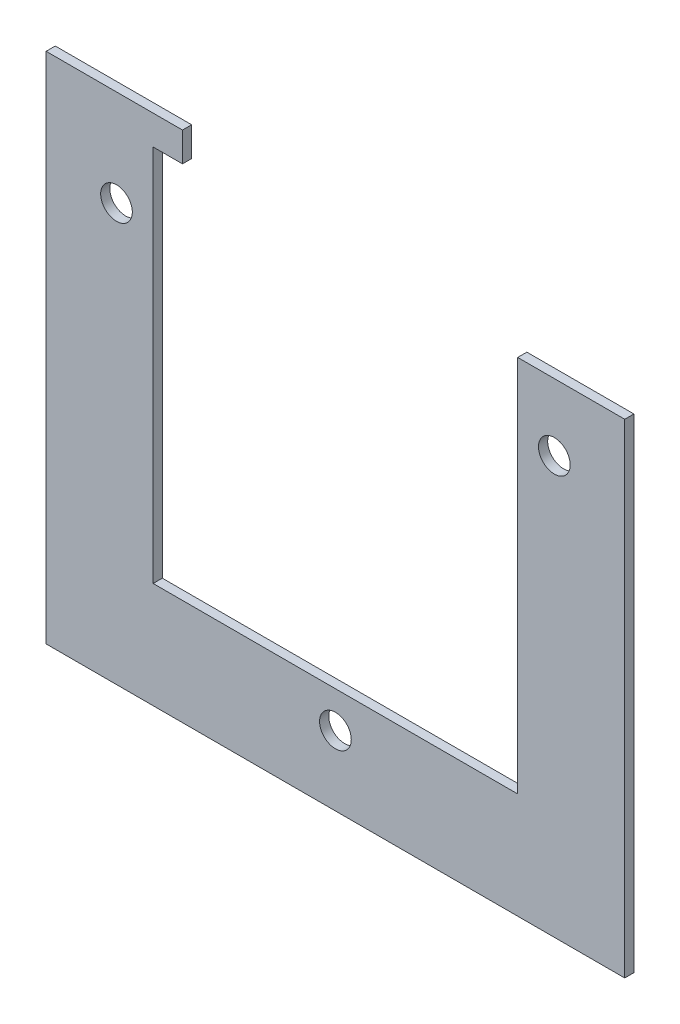
SolidWorks part; units mm, degrees
ref_plane "Front Plane" through (0, 0, 0) normal (0, 0, 1) x (1, 0, 0)
ref_plane "Top Plane" through (0, 0, 0) normal (0, 1, 0) x (1, 0, 0)
ref_plane "Right Plane" through (0, 0, 0) normal (1, 0, 0) x (0, 0, -1)
sketch "Sketch1" plane through (0, 0, 0) normal (0, 0, 1) x (1, 0, 0)
  line L0 (7520.0826, 3427.6123) -> (7529.3536, 3427.6123)
  line L1 (7479.2394, 3430.1523) -> (7491.0504, 3430.1523)
  line L2 (7520.0826, 3427.6123) -> (7520.0826, 3394.8717)
  line L3 (7529.3536, 3427.6123) -> (7529.3536, 3385.7023)
  line L4 (7520.0826, 3394.8717) -> (7488.5104, 3394.8717)
  line L5 (7529.3536, 3385.7023) -> (7479.2394, 3385.7023)
  line L6 (7488.5104, 3394.8717) -> (7488.5104, 3427.6123)
  line L7 (7479.2394, 3430.1523) -> (7479.2394, 3385.7023)
  line L8 (7491.0504, 3427.6123) -> (7491.0504, 3430.1523)
  line L9 (7491.0504, 3427.6123) -> (7488.5104, 3427.6123)
  circle A0 centre (7504.2965, 3391.7349) radius 1.3716
  circle A1 centre (7523.2576, 3421.8211) radius 1.3716
  circle A2 centre (7485.3354, 3421.8211) radius 1.3716
extrude "Boss-Extrude1" add sketch "Sketch1" along normal blind 0.7937
